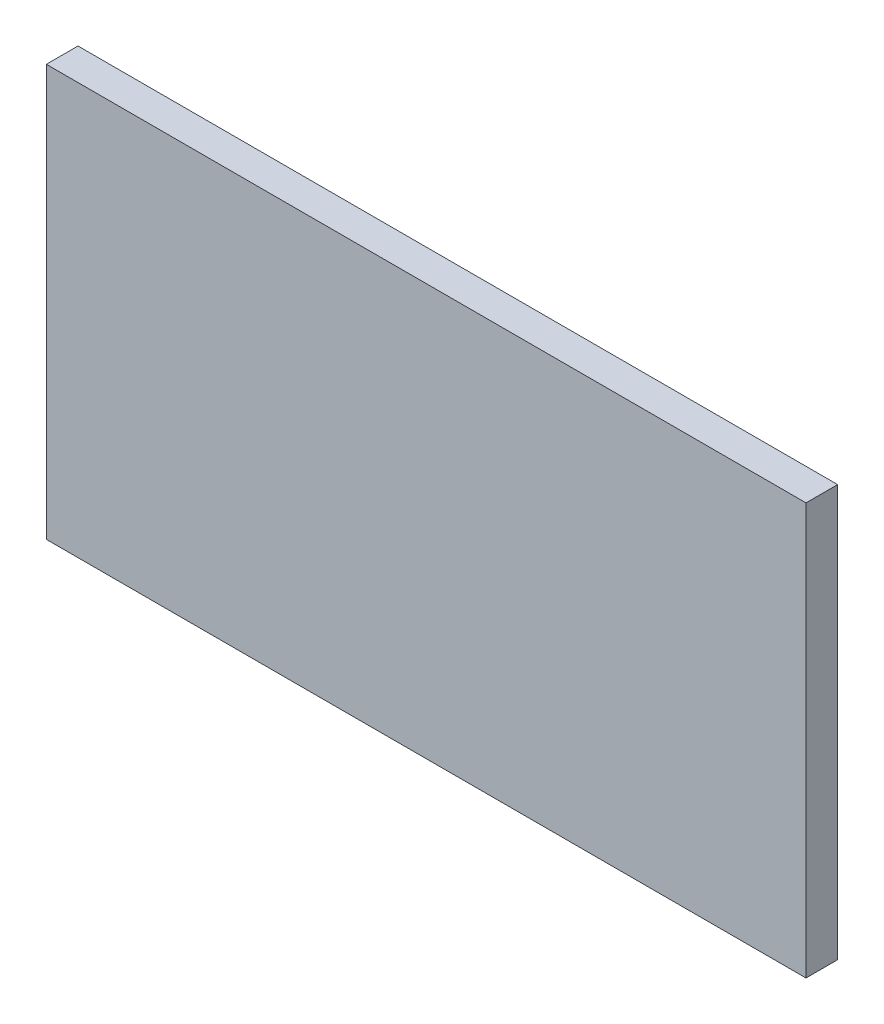
SolidWorks part; units mm, degrees
ref_plane "Спереди" through (0, 0, 0) normal (0, 0, 1) x (1, 0, 0)
ref_plane "Сверху" through (0, 0, 0) normal (0, 1, 0) x (1, 0, 0)
ref_plane "Справа" through (0, 0, 0) normal (1, 0, 0) x (0, 0, -1)
sketch "Sketch1" plane through (0, 0, 0) normal (0, 0, 1) x (1, 0, 0)
  line L1 (0, 0) -> (-24, 0)
  line L2 (0, 0) -> (0, 13)
  line L3 (0, 13) -> (-24, 13)
  line L4 (-24, 0) -> (-24, 13)
  dimension "D1" = 24
  dimension "D2" = 13
extrude "Boss-Extrude1" add sketch "Sketch1" along normal blind 1
